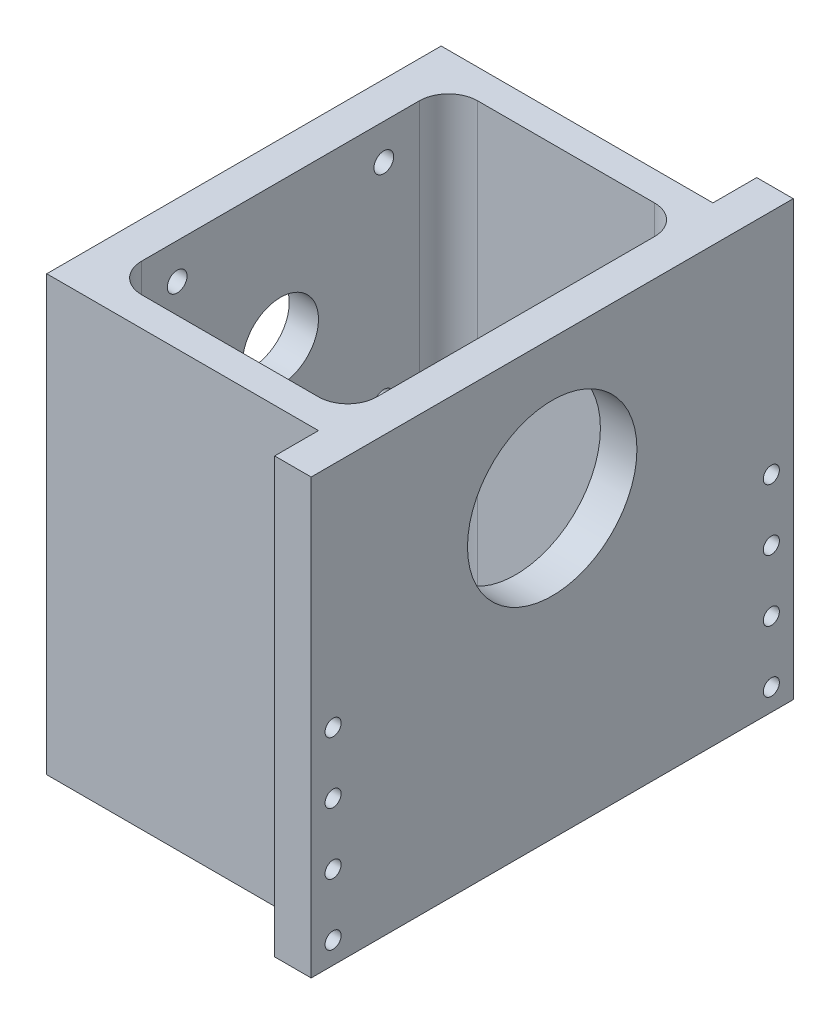
SolidWorks part; units mm, degrees
ref_plane "前视基准面" through (0, 0, 0) normal (0, 0, 1) x (1, 0, 0)
ref_plane "上视基准面" through (0, 0, 0) normal (0, 1, 0) x (1, 0, 0)
ref_plane "右视基准面" through (0, 0, 0) normal (1, 0, 0) x (0, 0, -1)
other "Configuration Table"
sketch "草图4" plane through (0, 0, 0) normal (0, 1, 0) x (1, 0, 0)
  line L1 (-233.3205, 0) -> (-233.3205, 152.4085) construction
  line L2 (-258.3205, -83.2249) -> (-258.3205, -53.2249)
  line L3 (-258.3205, -383.2249) -> (-233.3205, -383.2249)
  line L4 (-258.3205, -383.2249) -> (-258.3205, -353.2249)
  line L5 (-258.3205, -53.2249) -> (-233.3205, -53.2249)
  line L6 (-233.3205, -383.2249) -> (-233.3205, -53.2249)
  line L7 (-258.3205, -383.2249) -> (-233.3205, -53.2249) construction
  line L8 (-258.3205, -53.2249) -> (-233.3205, -383.2249) construction
  line L9 (-444.3205, -353.2249) -> (-258.3205, -353.2249)
  line L10 (-444.3205, -353.2249) -> (-444.3205, -83.2249)
  line L11 (-444.3205, -83.2249) -> (-258.3205, -83.2249)
  line L12 (-258.3205, -313.2249) -> (-258.3205, -123.2249)
  line L13 (-444.3205, -353.2249) -> (-258.3205, -83.2249) construction
  line L14 (-444.3205, -83.2249) -> (-258.3205, -353.2249) construction
  line L15 (-399.3205, -333.2249) -> (-278.3205, -333.2249)
  line L16 (-419.3205, -313.2249) -> (-419.3205, -123.2249)
  line L17 (-399.3205, -103.2249) -> (-278.3205, -103.2249)
  line L19 (-419.3205, -333.2249) -> (-258.3205, -103.2249) construction
  line L20 (-419.3205, -103.2249) -> (-258.3205, -333.2249) construction
  arc A0 (-258.3205, -123.2249) -> (-278.3205, -103.2249) centre (-278.3205, -123.2249) ccw
  arc A1 (-419.3205, -123.2249) -> (-399.3205, -103.2249) centre (-399.3205, -123.2249) cw
  arc A2 (-399.3205, -333.2249) -> (-419.3205, -313.2249) centre (-399.3205, -313.2249) cw
  arc A3 (-278.3205, -333.2249) -> (-258.3205, -313.2249) centre (-278.3205, -313.2249) ccw
  point P2 (-351.3205, -218.2249)
  point P3 (-564.102, -33.5961)
  point P4 (-245.8205, -218.2249)
  point P14 (-338.8205, -218.2249)
  dimension "D7" = 20
  dimension "D8" = 20
  dimension "D1" = 25
  dimension "D2" = 330
  dimension "D3" = 270
  dimension "D4" = 211
  dimension "D5" = 25
  dimension "D6" = 20
  dimension "D9" = 161
  dimension "D10" = 20
extrude "凸台-拉伸1" add sketch "草图4" along normal blind 297
sketch "草图6" plane through (-444.3205, 0, 0) normal (-1, 0, 0) x (0, 0, 1)
  line L0 (218.2249, 0) -> (218.2249, 202) construction
  line L2 (83.2249, 0) -> (353.2249, 0) construction
  circle A0 centre (218.2249, 202) radius 57.15
  dimension "D1" = 114.3
extrude "切除-拉伸1" cut sketch "草图6" against normal blind 5
sketch "草图7" plane through (-439.3205, 0, 0) normal (-1, 0, 0) x (0, 0, 1)
  circle A0 centre (218.2249, 202) radius 26
  dimension "D1" = 52
extrude "切除-拉伸2" cut sketch "草图7" against normal up to next
sketch "草图8" plane through (-233.3205, 0, 0) normal (1, 0, 0) x (0, 0, -1)
  line L0 (-218.2249, 0) -> (-218.2249, 202) construction
  line L1 (-383.2249, 0) -> (-53.2249, 0) construction
  circle A0 centre (-218.2249, 202) radius 58
  dimension "D1" = 116
extrude "切除-拉伸3" cut sketch "草图8" against normal up to next
sketch "草图10" plane through (-258.3205, 0, 0) normal (-1, 0, 0) x (0, 0, 1)
  line L0 (218.2249, 0) -> (218.2249, 141) construction
  circle A0 centre (368.2249, 15) radius 5.5
  circle A1 centre (368.2249, 57) radius 5.5
  circle A2 centre (368.2249, 99) radius 5.5
  circle A3 centre (368.2249, 141) radius 5.5
  circle A4 centre (68.2249, 141) radius 5.5
  circle A5 centre (68.2249, 15) radius 5.5
  circle A6 centre (68.2249, 57) radius 5.5
  circle A7 centre (68.2249, 99) radius 5.5
  dimension "D1" = 4
extrude "切除-拉伸4" cut sketch "草图10" against normal up to next
sketch "草图11" plane through (-444.3205, 0, 0) normal (-1, 0, 0) x (0, 0, 1)
  circle A0 centre (218.2249, 202) radius 100 construction
  point P9 (147.5149, 272.7114)
  dimension "D1" = 200
hole_wizard "M12 间隙孔1" positions "草图16" profile "草图17" hole size "M12" standard "GB"
sketch "草图16" plane through (-444.3205, 0, 0) normal (-1, 0, 0) x (0, 0, 1)
  point P0 (147.5149, 272.7114)
sketch "草图17" plane through (-444.3205, 272.7114, 147.5149) normal (0, 1, 0) x (0, 0, 1)
  line L0 (0, 0) -> (0, 25)
  line L1 (0, 25) -> (6.75, 25)
  line L2 (6.75, 25) -> (6.75, 0)
  line L5 (6.75, 0) -> (0, 0)
  line L11 (0, -6.35) -> (0, 107.95) construction
  dimension "通孔孔直径" = 13.5
  dimension "通孔孔深度" = 25
pattern_circular "阵列(圆周)1" count 4 every 90 about axis through (0, 202, 218.2249) along (1, 0, 0) of "M12 间隙孔1"
